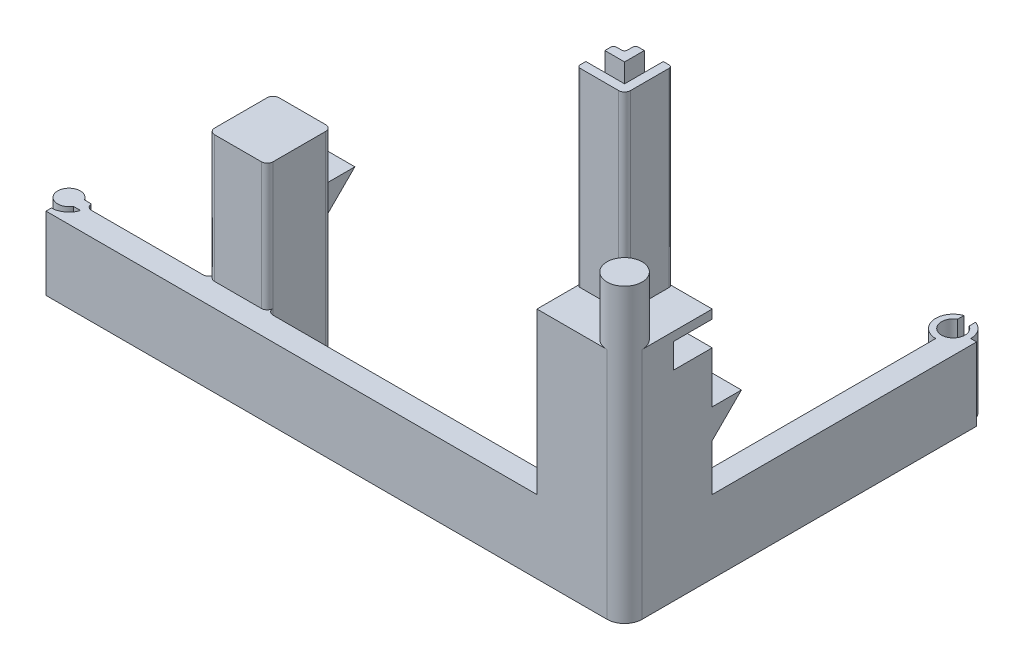
SolidWorks part; units mm, degrees
ref_plane "Front Plane" through (0, 0, 0) normal (0, 0, 1) x (1, 0, 0)
ref_plane "Top Plane" through (0, 0, 0) normal (0, 1, 0) x (1, 0, 0)
ref_plane "Right Plane" through (0, 0, 0) normal (1, 0, 0) x (0, 0, -1)
sketch "Sketch1" plane through (0, 0, 0) normal (0, 1, 0) x (1, 0, 0)
  line L1 (-15, -15) -> (15, -15)
  line L2 (-15, -15) -> (-15, 15)
  line L3 (-15, 15) -> (15, 15)
  line L4 (15, -15) -> (15, 15)
  line L5 (-15, -15) -> (15, 15) construction
  line L6 (-15, 15) -> (15, -15) construction
  point P0 (0, 0)
  dimension "D1" = 30
extrude "Boss-Extrude1" add sketch "Sketch1" along normal blind 80
sketch "Sketch2" plane through (0, 80, 0) normal (0, 1, 0) x (1, 0, 0)
  line L0 (-15, -15) -> (15, -15) construction
  line L1 (15, -15) -> (15, 15) construction
  circle A0 centre (9, -9) radius 6
  dimension "D1" = 12
extrude "Boss-Extrude2" add sketch "Sketch2" along normal blind 20
sketch "Sketch3" plane through (0, 80, 0) normal (0, 1, 0) x (1, 0, 0)
  line L2 (9, -15) -> (15, -15)
  line L4 (15, -15) -> (15, -9)
  circle A1 centre (9, -9) radius 6
  arc A4 (9, -15) -> (15, -9) centre (9, -9) ccw
  dimension "D1" = 0
extrude "Cut-Extrude1" cut sketch "Sketch3" against normal through all
sketch "Sketch4" plane through (0, 80, 0) normal (0, 1, 0) x (1, 0, 0)
  line L0 (1.25, 11.25) -> (1.25, 15)
  line L1 (-8.25, 11.25) -> (-1.75, 11.25) construction
  line L2 (-8.25, 11.25) -> (-8.25, 8.25)
  line L5 (1.25, 15) -> (-1.75, 15)
  line L6 (-1.75, 1.75) -> (-11.25, 1.75)
  line L8 (-8.25, 8.25) -> (-11.25, 8.25)
  line L9 (-11.25, 1.75) -> (-11.25, 8.25) construction
  line L10 (-1.75, 11.25) -> (-1.75, 1.75)
  line L11 (-11.25, -1.25) -> (1.25, -1.25)
  line L12 (1.25, -1.25) -> (1.25, 11.25)
  line L13 (1.25, 11.25) -> (-1.75, 11.25) construction
  line L14 (-11.25, 1.75) -> (-11.25, -1.25) construction
  line L15 (-11.25, 8.25) -> (-11.25, 11.25) construction
  line L16 (-11.25, 11.25) -> (-11.25, 15)
  line L17 (15, 15) -> (-15, 15) construction
  line L18 (-11.25, 11.25) -> (-8.25, 11.25) construction
  line L19 (-11.25, 15) -> (-8.25, 15)
  line L20 (-8.25, 15) -> (-8.25, 11.25)
  line L21 (-11.25, 8.25) -> (-15, 8.25)
  line L22 (-15, 15) -> (-15, -15) construction
  line L23 (-15, 8.25) -> (-15, 11.25)
  line L24 (-15, 11.25) -> (-11.25, 11.25)
  line L25 (-1.75, 15) -> (-1.75, 11.25)
  line L26 (-11.25, 1.75) -> (-15, 1.75)
  line L27 (-15, 1.75) -> (-15, -1.25)
  line L28 (-15, -1.25) -> (-11.25, -1.25)
  dimension "D1" = 6.5
  dimension "D3" = 3
  dimension "D4" = 3.75
extrude "Boss-Extrude3" add sketch "Sketch4" along normal blind 65
sketch "Sketch6" plane through (0, 0, 0) normal (0, -1, 0) x (1, 0, 0)
  line L1 (15, -15) -> (7, -15)
  line L2 (15, -15) -> (15, -105.5)
  line L3 (15, -105.5) -> (13, -105.5)
  line L4 (7, -15) -> (7, -99.5)
  arc A1 (7, -99.5) -> (13, -105.5) centre (7, -105.5) ccw
  dimension "D3" = 12
  dimension "D1" = 90.5
  dimension "D2" = 8
extrude "Boss-Extrude5" add sketch "Sketch6" against normal blind 2
sketch "Sketch7" plane through (0, 2, 0) normal (0, 1, 0) x (1, 0, 0)
  line L0 (7, 109.5) -> (7, 111.5) construction
  line L1 (9, 111.1569) -> (9, 108.9641)
  line L2 (5, 111.1569) -> (5, 108.9641)
  line L3 (7, 101.5) -> (7, 99.5) construction
  line L4 (15, 105.5) -> (13, 105.5)
  line L5 (15, 105.5) -> (15, 15)
  line L6 (15, 15) -> (7, 15)
  line L7 (7, 15) -> (7, 99.5) construction
  line L8 (15, 15) -> (1.25, 15) construction
  line L9 (7, 15) -> (7, 99.5)
  arc A0 (5, 111.1569) -> (7, 99.5) centre (7, 105.5) ccw
  arc A1 (13, 105.5) -> (7, 99.5) centre (7, 105.5) ccw construction
  arc A2 (5, 108.9641) -> (9, 108.9641) centre (7, 105.5) ccw
  arc A3 (13, 105.5) -> (9, 111.1569) centre (7, 105.5) ccw
  dimension "D1" = 2
  dimension "D2" = 2
extrude "Boss-Extrude6" add sketch "Sketch7" along normal offset from surface (23 mm away) 25 up to face at (3.75, 0, -38.4375)
sketch "Sketch9" plane through (0, 0, 0) normal (0, -1, 0) x (1, 0, 0)
  line L0 (15, -15) -> (7, -15) construction
  line L1 (-15, 15) -> (-183.175, 15) construction
  line L2 (-15, 15) -> (-15, 7)
  line L3 (-15, 7) -> (-177.175, 7) construction
  line L4 (-183.175, 15) -> (-183.175, 13.1746) construction
  line L5 (-187.05, 7) -> (-187.175, 7) construction
  line L6 (-179.175, 7) -> (-177.175, 7) construction
  line L7 (-177.175, 9) -> (-179.856, 9) construction
  line L8 (7, -109.5) -> (7, -111.5) construction
  line L9 (9, -111.1569) -> (5, -111.1569) construction
  line L10 (-177.175, 5) -> (-179.856, 5) construction
  line L11 (-177.175, 9) -> (-177.175, 5) construction
  line L12 (-179.7978, 8.9) -> (-177.3, 8.9)
  line L13 (-179.7978, 5.1) -> (-177.175, 5.1) construction
  line L14 (-177.175, 5.1) -> (-177.175, 7) construction
  line L15 (-177.175, 8.9) -> (-177.3, 8.9) construction
  line L16 (-183.05, 15) -> (-183.05, 13.1733)
  line L17 (-183.05, 14.0867) -> (-183.175, 14.0873) construction
  line L18 (-183.05, 15) -> (-15, 15)
  line L19 (-177.175, 5.1) -> (-177.175, 7) construction
  line L20 (-15, 7) -> (-177.175, 7)
  line L21 (-177.4838, 5.1) -> (-179.7978, 5.1)
  circle A0 centre (-183.175, 7) radius 4 construction
  arc A1 (9, -108.9641) -> (5, -108.9641) centre (7, -105.5) ccw construction
  arc A2 (-179.7978, 8.9) -> (-179.7978, 5.1) centre (-183.175, 7) ccw
  arc A4 (-177.3, 8.9) -> (-183.175, 13.1746) centre (-183.175, 7) ccw construction
  arc A6 (-177.3, 8.9) -> (-183.05, 13.1733) centre (-183.175, 7) ccw
  arc A7 (-177.4838, 5.1) -> (-177.175, 7) centre (-183.175, 7) ccw
  arc A8 (7, -99.5) -> (5, -111.1569) centre (7, -105.5) ccw construction
  dimension "D1" = 168.175
  dimension "D2" = 0.125
  dimension "D3" = 1.9
extrude "Boss-Extrude7" add sketch "Sketch9" against normal blind 25
fillet "Fillet1" radius 2 1 edges at (-177.175, 12.5, 7)
sketch "Sketch11" plane through (0, 0, 0) normal (0, -1, 0) x (1, 0, 0)
  line L0 (-177.3, 8.9) -> (-177.425, 8.9) construction
  line L2 (-177.3, 8.9) -> (-179.7978, 8.9) construction
  line L3 (-187.05, 7) -> (-187.175, 7) construction
  circle A0 centre (-183.175, 7) radius 6.0558
  arc A5 (-179.7978, 8.9) -> (-179.7978, 5.1) centre (-183.175, 7) ccw construction
extrude "Cut-Extrude2" cut sketch "Sketch11" against normal offset from surface (2.125 mm away) 0.125 up to face at (7, 2, -108.2802) offset beyond the face yes
sketch "Sketch12" plane through (15, 0, 0) normal (1, 0, 0) x (0, 0, -1)
  line L0 (15, 80) -> (15, 25) construction
  line L1 (15, 77) -> (1.75, 77)
  line L2 (15, 77) -> (15, 68.5)
  line L3 (15, 68.5) -> (1.75, 68.5)
  line L4 (1.75, 77) -> (1.75, 68.5)
  line L7 (-9, 80) -> (15, 80) construction
  line L9 (1.75, 145) -> (1.75, 80) construction
  dimension "D1" = 3
  dimension "D2" = 8.5
extrude "Cut-Extrude3" cut sketch "Sketch12" against normal through all both
sketch "Sketch13" plane through (0, 0, 15) normal (0, 0, 1) x (1, 0, 0)
  line L0 (15, 0) -> (-187.05, 0) construction
  line L1 (-187.05, 25) -> (-187.05, 2.125) construction
  line L2 (-183.05, 0) -> (9, 0) construction
fillet "Fillet2" radius 2 1 edges at (1.25, 112.5, 1.25)
sketch "Sketch15" plane through (0, 80, 0) normal (0, 1, 0) x (1, 0, 0)
  line L4 (-11.25, 11.25) -> (-11.25, 15)
  line L5 (-11.25, 15) -> (-15, 15)
  line L6 (-15, 15) -> (-15, 11.25)
  line L7 (-15, 11.25) -> (-11.25, 11.25)
  line L8 (-11.25, 11.25) -> (-11.25, 15)
  line L9 (-11.25, 15) -> (-15, 15)
  line L10 (-15, 15) -> (-15, 11.25)
  line L11 (-15, 11.25) -> (-11.25, 11.25)
  dimension "D1" = 0
extrude "Cut-Extrude4" cut sketch "Sketch15" against normal up to next
fillet "Fillet3" radius 1 5 edges at (-15, 112.5, 1.25) (1.25, 112.5, -15) (-11.25, 111, -15) (-11.25, 111, -11.25) (-15, 111, -11.25)
sketch "Sketch16" plane through (0, 0, 0) normal (0, -1, 0) x (1, 0, 0)
  line L0 (-175.429, 7) -> (-15, 7) construction
  line L1 (-115.3218, 7) -> (-135.3218, 7)
  line L2 (-115.3218, 7) -> (-115.3218, -15)
  line L3 (-115.3218, -15) -> (-135.3218, -15)
  line L4 (-135.3218, 7) -> (-135.3218, -15)
  line L5 (-95.2145, -7) -> (-95.2145, 15) construction
  line L6 (15, 15) -> (-187.05, 15) construction
  line L7 (-15, -15) -> (15, -15) construction
  line L8 (-175.429, 7) -> (-95.2145, 7) construction
  point P10 (-95.2145, 7)
  point P13 (-135.3218, 7)
  dimension "D1" = 20
extrude "Boss-Extrude8" add sketch "Sketch16" against normal up to surface (68.5 mm away) up to face at (0, 68.5, -8.375)
sketch "Sketch17" plane through (0, 0, 0) normal (0, -1, 0) x (1, 0, 0)
  line L0 (-135.3218, 7) -> (-115.3218, 7) construction
  line L1 (-132.8218, -12.5) -> (-117.8218, -12.5)
  line L2 (-132.8218, -12.5) -> (-132.8218, 4.5)
  line L3 (-132.8218, 4.5) -> (-117.8218, 4.5)
  line L4 (-117.8218, -12.5) -> (-117.8218, 4.5)
  line L5 (-115.3218, 7) -> (-115.3218, -15) construction
  line L6 (-115.3218, -15) -> (-135.3218, -15) construction
  line L7 (-135.3218, -15) -> (-135.3218, 7) construction
  line L8 (-132.8218, 4.5) -> (-132.8218, 7) construction
  line L10 (-135.3218, 4.5) -> (-132.8218, 4.5) construction
  line L11 (-117.8218, 4.5) -> (-115.3218, 4.5) construction
  line L12 (-132.8218, -15) -> (-132.8218, -12.5) construction
  dimension "D1" = 2.5
fillet "Fillet4" radius 2 4 edges at (-115.3218, 12.5, 7) (-135.3218, 12.5, 7) (-115.3218, 34.25, -15) (-135.3218, 34.25, -15)
fillet "Fillet5" radius 2 2 edges at (-115.3218, 46.75, 7) (-135.3218, 46.75, 7)
extrude "Cut-Extrude5" cut sketch "Sketch17" against normal offset from surface (66 mm away) 2.5 up to face at (-125.3218, 68.5, -4)
chamfer "Chamfer1" distance 7 angle 45 4 edges at (-125.3218, 66, 4.5) (-117.8218, 66, -4) (-125.3218, 66, -12.5) (-132.8218, 66, -4)
sketch "Sketch18" plane through (15, 0, 0) normal (1, 0, 0) x (0, 0, -1)
  line L0 (15, 68.5) -> (15, 51) construction
  line L1 (15, 68.5) -> (15, 25) construction
  line L2 (15, 51) -> (15, 41)
  line L3 (15, 41) -> (25, 51)
  line L4 (25, 51) -> (15, 51)
  dimension "D1" = 17.5
  dimension "D2" = 10
extrude "Boss-Extrude9" add sketch "Sketch18" against normal up to surface (30 mm away) up to face at (-15, 77.5625, -1.8438)
ref_plane "Plane1" through (-125.3218, 0, 0) normal (-1, 0, 0) x (0, 0, 1)
sketch "Sketch19" plane through (-125.3218, 0, 0) normal (-1, 0, 0) x (0, 0, 1)
  line L3 (-15, 41) -> (-15, 51)
  line L4 (-25, 51) -> (-15, 41)
  line L5 (-15, 51) -> (-25, 51)
  line L6 (-15, 41) -> (-15, 51)
  line L7 (-25, 51) -> (-15, 41)
  line L8 (-15, 51) -> (-25, 51)
  dimension "D1" = 0
extrude "Boss-Extrude10" add sketch "Sketch19" against normal up to vertex and the other way up to vertex
